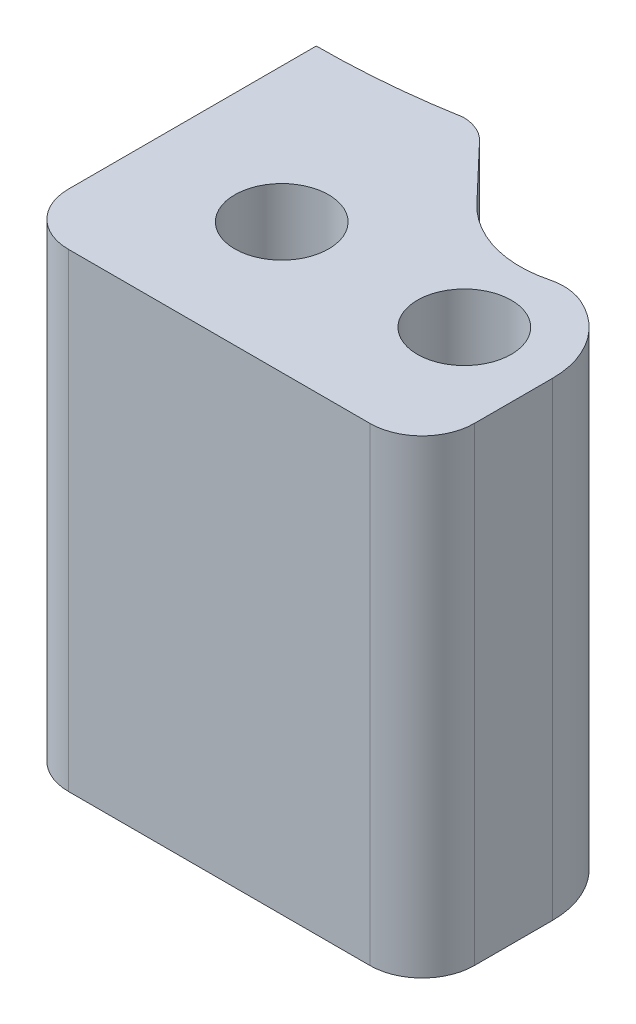
SolidWorks part; units mm, degrees
ref_plane "前视基准面" through (0, 0, 0) normal (0, 0, 1) x (1, 0, 0)
ref_plane "上视基准面" through (0, 0, 0) normal (0, 1, 0) x (1, 0, 0)
ref_plane "右视基准面" through (0, 0, 0) normal (1, 0, 0) x (0, 0, -1)
other "Configuration Table"
sketch "草图1" plane through (0, 0, 0) normal (0, 1, 0) x (1, 0, 0)
  line L0 (0, -41.32) -> (0, -31.32)
  line L1 (31.32, -41.32) -> (31.32, 0) construction
  line L2 (0, -41.32) -> (31.32, -41.32) construction
  line L3 (0, 0) -> (0, -31.32) construction
  line L4 (5.176, -36.32) -> (12.176, -36.32) construction
  line L5 (5.176, -36.32) -> (5.176, -5.176) construction
  line L6 (5.176, -5.176) -> (0, 0) construction
  line L7 (0, 0) -> (31.32, 0) construction
  line L8 (6.2779, -29.8394) -> (8.3336, -31.9969)
  line L9 (15.5597, -36.32) -> (15.5597, -41.32)
  line L10 (12.176, -36.32) -> (15.5597, -36.32) construction
  line L11 (0, -31.32) -> (0, -29.82)
  line L12 (0, -41.32) -> (15.5597, -41.32)
  line L13 (11.2295, -29.2376) -> (12.6637, -32.9717) construction
  line L14 (0, 0) -> (11.2295, -29.2376) construction
  arc A0 (0, -31.32) -> (31.32, 0) centre (0, 0) ccw construction
  arc A1 (0, -29.82) -> (5.176, -29.3673) centre (0, 0) ccw
  circle A3 centre (5.176, -36.32) radius 1.8
  circle A4 centre (12.176, -36.32) radius 1.8
  circle A5 centre (5.176, -30.8893) radius 1.5 construction
  circle A6 centre (11.2295, -29.2376) radius 1.5 construction
  circle A7 centre (16.8323, -26.4124) radius 1.5 construction
  circle A8 centre (21.7595, -22.527) radius 1.5 construction
  circle A9 centre (25.8133, -17.7374) radius 1.5 construction
  circle A10 centre (28.831, -12.2359) radius 1.5 construction
  circle A11 centre (30.6914, -6.2432) radius 1.5 construction
  circle A12 centre (31.32, 0) radius 1.5 construction
  arc A13 (5.176, -29.3673) -> (6.2779, -29.8394) centre (5.176, -30.8893) cw
  arc A14 (8.3336, -31.9969) -> (12.2249, -33.1118) centre (11.2295, -29.2376) ccw
  arc A15 (13.5127, -33.2116) -> (15.5597, -36.32) centre (12.176, -36.32) cw
  arc A16 (12.2249, -33.1118) -> (13.5127, -33.2116) centre (12.7226, -35.0489) cw
  point P32 (0, 0)
  dimension "D1" = 31.32
  dimension "D2" = 3
  dimension "D6" = 3.6
  dimension "D10" = 4
  dimension "D11" = 2
  dimension "D3" = 10
  dimension "D4" = 7
  dimension "D5" = 5
  dimension "D7" = 45
  dimension "D8" = 7.32
  dimension "D9" = 8
extrude "凸台-拉伸1" add sketch "草图1" along normal blind 18
fillet "圆角1" radius 2 2 edges at (15.5597, 9, 41.32) (0, 9, 41.32)
